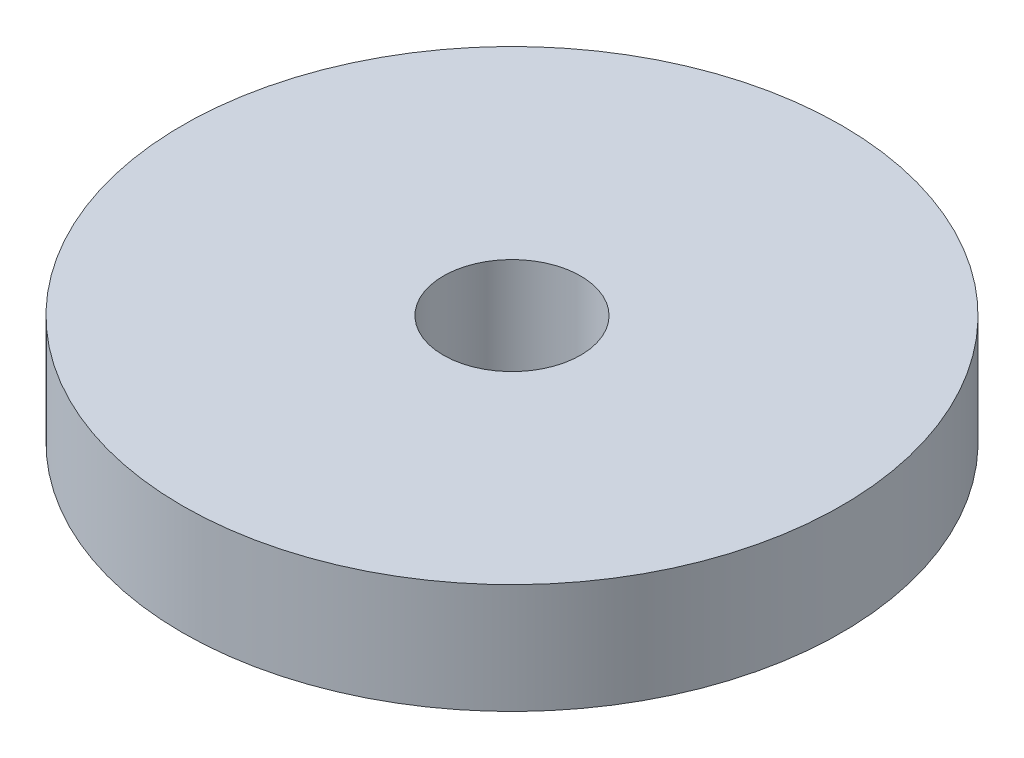
SolidWorks part; units mm, degrees
ref_plane "Front Plane" through (0, 0, 0) normal (0, 0, 1) x (1, 0, 0)
ref_plane "Top Plane" through (0, 0, 0) normal (0, 1, 0) x (1, 0, 0)
ref_plane "Right Plane" through (0, 0, 0) normal (1, 0, 0) x (0, 0, -1)
sketch "Sketch1" plane through (0, 0, 0) normal (0, 1, 0) x (1, 0, 0)
  circle A0 centre (0, 0) radius 15.24
  circle A1 centre (0, 0) radius 3.175
extrude "Boss-Extrude1" add sketch "Sketch1" along normal blind 5.08
